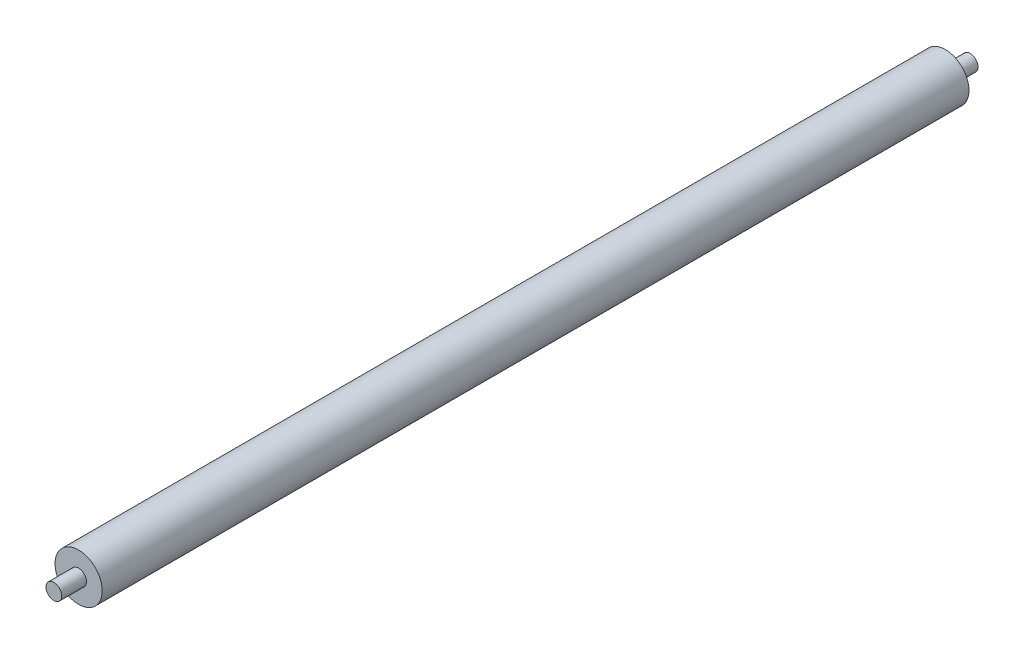
SolidWorks part; units mm, degrees
ref_plane "Alzado" through (0, 0, 0) normal (0, 0, 1) x (1, 0, 0)
ref_plane "Planta" through (0, 0, 0) normal (0, 1, 0) x (1, 0, 0)
ref_plane "Vista lateral" through (0, 0, 0) normal (1, 0, 0) x (0, 0, -1)
sketch "Sketch1" plane through (0, 0, 0) normal (0, 0, 1) x (1, 0, 0)
  circle A0 centre (0, 0) radius 19.05
  dimension "D1" = 38.1
extrude "Boss-Extrude1" add sketch "Sketch1" along normal mid plane 700
sketch "Sketch2" plane through (0, 0, 0) normal (0, 0, 1) x (1, 0, 0)
  circle A0 centre (0, 0) radius 6.35
  dimension "D1" = 12.7
extrude "Boss-Extrude2" add sketch "Sketch2" along normal mid plane 740 contours A0
